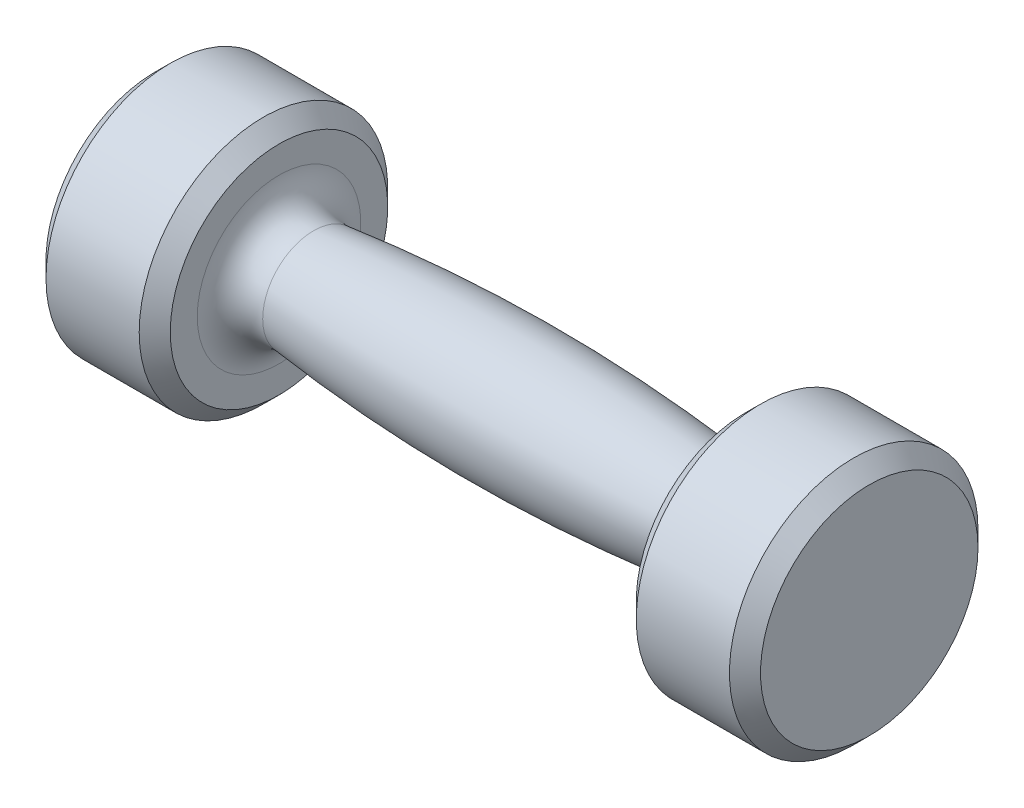
SolidWorks part; units mm, degrees
ref_plane "Front Plane" through (0, 0, 0) normal (0, 0, 1) x (1, 0, 0)
ref_plane "Top Plane" through (0, 0, 0) normal (0, 1, 0) x (1, 0, 0)
ref_plane "Right Plane" through (0, 0, 0) normal (1, 0, 0) x (0, 0, -1)
sketch "Sketch1" plane through (0, 0, 0) normal (1, 0, 0) x (0, 0, -1)
  circle A1 centre (0, 0) radius 15
  dimension "D1" = 30
extrude "Boss-Extrude1" add sketch "Sketch1" along normal mid plane 230
sketch "Sketch2" plane through (115, 0, 0) normal (1, 0, 0) x (0, 0, -1)
  circle A0 centre (0, 0) radius 40
  dimension "D1" = 80
extrude "Boss-Extrude2" add sketch "Sketch2" against normal blind 40
sketch "Sketch3" plane through (-115, 0, 0) normal (-1, 0, 0) x (0, 0, 1)
  circle A0 centre (0, 0) radius 40
  dimension "D1" = 80
extrude "Boss-Extrude3" add sketch "Sketch3" against normal blind 40 contours A0
sketch "Sketch5" plane through (0, 0, 0) normal (0, 0, 1) x (1, 0, 0)
  line L0 (-125.3967, 0) -> (123.9691, 0) construction
  line L1 (-75, 15) -> (75, 15)
  arc A0 (-75, 15) -> (75, 15) centre (0, -545) cw
  point P7 (0, 20)
  dimension "D1" = 20
revolve "Revolve1" add sketch "Sketch5" angle 360 about L0
chamfer "Chamfer1" distance 5 angle 45 4 edges at (75, 0, -40) (115, 0, -40) (-75, 0, 40) (-115, 0, 40)
fillet "Fillet1" radius 10 2 edges at (75, 0, 15) (-75, 0, 15)
